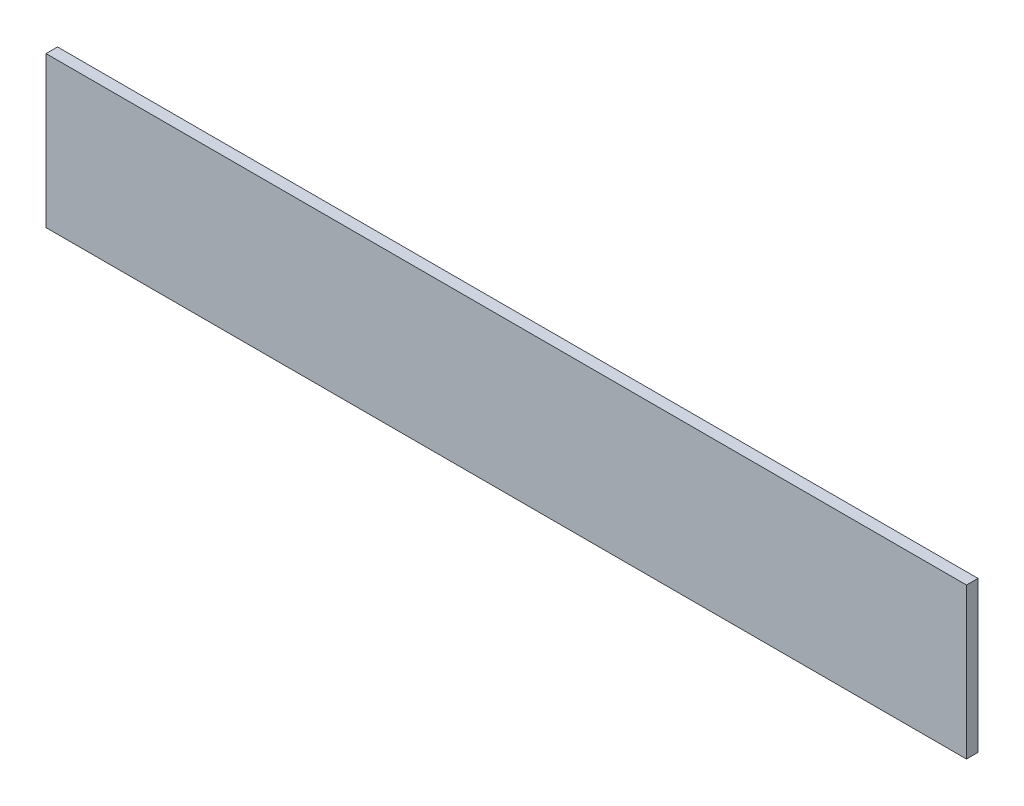
SolidWorks part; units mm, degrees
ref_plane "Front Plane" through (0, 0, 0) normal (0, 0, 1) x (1, 0, 0)
ref_plane "Top Plane" through (0, 0, 0) normal (0, 1, 0) x (1, 0, 0)
ref_plane "Right Plane" through (0, 0, 0) normal (1, 0, 0) x (0, 0, -1)
sketch "Sketch1" plane through (0, 0, 0) normal (0, 0, 1) x (1, 0, 0)
  line L0 (-40, 0) -> (0, 0) construction
  line L1 (-40, 6.55) -> (40, 6.55)
  line L2 (-40, 6.55) -> (-40, -6.55)
  line L3 (-40, -6.55) -> (40, -6.55)
  line L4 (40, 6.55) -> (40, -6.55)
  line L5 (0, 0) -> (0, 6.55) construction
  dimension "D1" = 13.1
  dimension "85" = 80
extrude "Boss-Extrude1" add sketch "Sketch1" along normal blind 1
